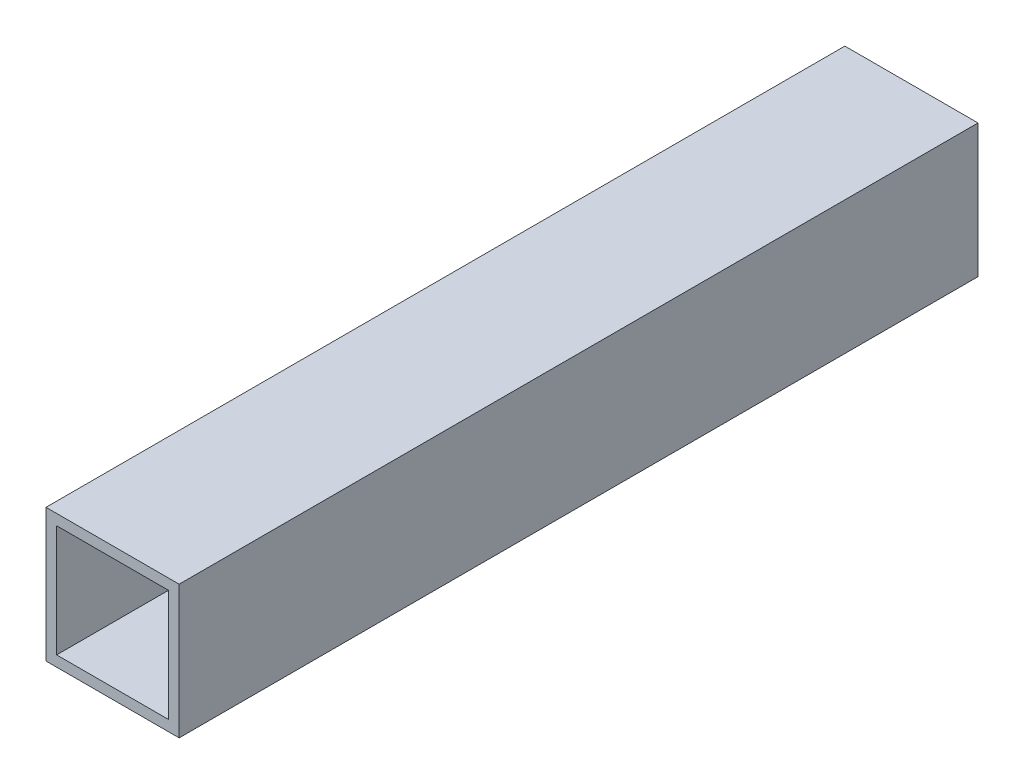
SolidWorks part; units mm, degrees
ref_plane "Ebene vorne" through (0, 0, 0) normal (0, 0, 1) x (1, 0, 0)
ref_plane "Ebene oben" through (0, 0, 0) normal (0, 1, 0) x (1, 0, 0)
ref_plane "Ebene rechts" through (0, 0, 0) normal (1, 0, 0) x (0, 0, -1)
sketch "Skizze1" plane through (0, 0, 0) normal (0, 0, 1) x (1, 0, 0)
  line L0 (-10.5, 10.5) -> (10.5, 10.5)
  line L1 (-12.5, 12.5) -> (12.5, 12.5)
  line L2 (-12.5, 12.5) -> (-12.5, -12.5)
  line L3 (-12.5, -12.5) -> (12.5, -12.5)
  line L4 (12.5, 12.5) -> (12.5, -12.5)
  line L5 (-12.5, 12.5) -> (12.5, -12.5) construction
  line L6 (-12.5, -12.5) -> (12.5, 12.5) construction
  line L7 (10.5, 10.5) -> (10.5, -10.5)
  line L8 (-10.5, -10.5) -> (10.5, -10.5)
  line L9 (-10.5, 10.5) -> (-10.5, -10.5)
  point P0 (0, 0)
  dimension "D1" = 25
  dimension "D2" = 2
extrude "Aufsatz-Linear austragen1" add sketch "Skizze1" along normal blind 150
